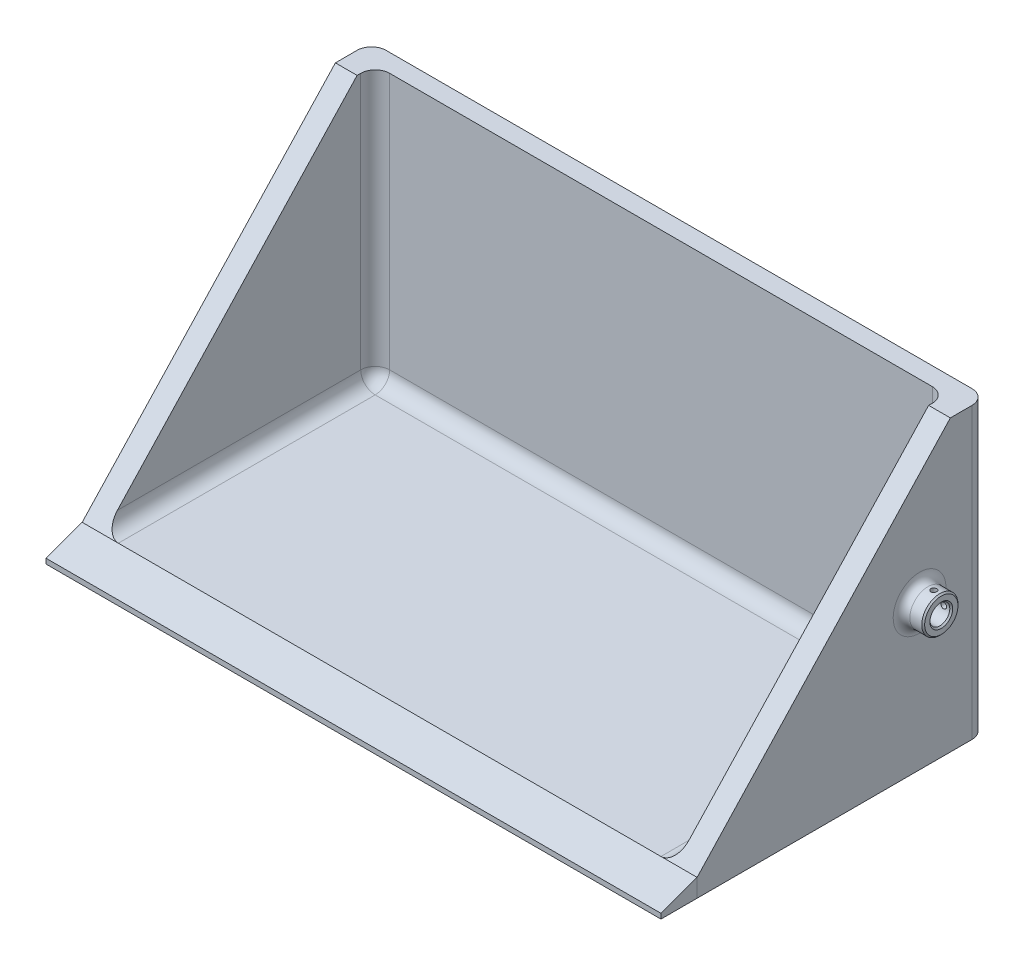
SolidWorks part; units mm, degrees
ref_plane "Front Plane" through (0, 0, 0) normal (0, 0, 1) x (1, 0, 0)
ref_plane "Top Plane" through (0, 0, 0) normal (0, 1, 0) x (1, 0, 0)
ref_plane "Right Plane" through (0, 0, 0) normal (1, 0, 0) x (0, 0, -1)
sketch "Sketch1" plane through (0, 0, 0) normal (0, 1, 0) x (1, 0, 0)
  line L1 (-107.95, 50.8) -> (107.95, 50.8)
  line L2 (-107.95, 50.8) -> (-107.95, -50.8)
  line L3 (-107.95, -50.8) -> (107.95, -50.8)
  line L4 (107.95, 50.8) -> (107.95, -50.8)
  line L5 (-107.95, 50.8) -> (107.95, -50.8) construction
  line L6 (-107.95, -50.8) -> (107.95, 50.8) construction
  point P0 (0, 0)
  dimension "D1" = 215.9
  dimension "D2" = 101.6
extrude "Boss-Extrude1" add sketch "Sketch1" along normal mid plane 6.35
sketch "Sketch3" plane through (-107.95, 0, 0) normal (-1, 0, 0) x (0, 0, 1)
  line L0 (-50.8, 3.175) -> (-50.8, 98.425)
  line L1 (-50.8, 98.425) -> (-38.1, 98.425)
  line L2 (-38.1, 98.425) -> (50.8, 3.175)
  line L3 (50.8, 3.175) -> (-50.8, 3.175)
  line L4 (-50.8, -3.175) -> (50.8, -3.175) construction
  dimension "D1" = 101.6
  dimension "D2" = 12.7
extrude "Boss-Extrude2" add sketch "Sketch3" against normal blind 7.62
mirror "Mirror1" about plane through (0, 0, 0) normal (1, 0, 0) of "Boss-Extrude2"
sketch "Sketch4" plane through (0, 3.175, 0) normal (0, 1, 0) x (1, 0, 0)
  line L0 (-100.33, 50.8) -> (100.33, 50.8)
  line L1 (100.33, 50.8) -> (100.33, 44.45)
  line L2 (100.33, 44.45) -> (-100.33, 44.45)
  line L3 (-100.33, 44.45) -> (-100.33, 50.8)
  dimension "D1" = 6.35
extrude "Boss-Extrude3" add sketch "Sketch4" along normal up to surface (95.25 mm away) up to face at (-104.14, 98.425, -44.45)
sketch "Sketch5" plane through (-107.95, 0, 0) normal (-1, 0, 0) x (0, 0, 1)
  line L1 (63.5, -3.175) -> (50.8, -3.175)
  line L2 (50.8, -3.175) -> (50.8, 3.175)
  line L3 (-50.8, 98.425) -> (-50.8, -3.175) construction
  line L4 (50.8, 3.175) -> (63.5, -1.397)
  line L5 (63.5, -1.397) -> (63.5, -3.175)
  dimension "D1" = 114.3
  dimension "D2" = 1.778
extrude "Boss-Extrude4" add sketch "Sketch5" along direction (1, 0, 0) on the side against the normal up to surface (215.9 mm away) separate body
fillet "Fillet2" radius 5.08 5 edges at (100.33, 3.175, 3.175) (100.33, 50.8, -44.45) (0, 3.175, -44.45) (-100.33, 3.175, 3.175) (-100.33, 50.8, -44.45)
fillet "Fillet3" radius 5.08 2 edges at (107.95, 47.625, -50.8) (-107.95, 47.625, -50.8)
sketch "Sketch6" plane through (107.95, 0, 0) normal (1, 0, 0) x (0, 0, -1)
  line L0 (-50.8, -3.175) -> (45.72, -3.175) construction
  line L1 (50.8, 98.425) -> (50.8, -3.175) construction
  circle A0 centre (27.305, 47.625) radius 3.4925
  circle A1 centre (27.305, 47.625) radius 6.35
  dimension "D1" = 6.985
  dimension "D2" = 12.7
  dimension "D3" = 50.8
  dimension "D4" = 23.495
extrude "Boss-Extrude5" add sketch "Sketch6" along normal blind 7.62
fillet "Fillet4" radius 2.921 1 edges at (107.95, 47.625, -20.955)
chamfer "Chamfer1" distance 0.508 angle 45 2 edges at (115.57, 47.625, -30.7975) (115.57, 47.625, -33.655)
ref_plane "setscrew_lhs_plane" through (0, 53.975, 0) normal (0, 1, 0) x (1, 0, 0)
sketch "Sketch7" plane through (0, 53.975, 0) normal (0, 1, 0) x (1, 0, 0)
  line L0 (110.871, 20.955) -> (115.062, 20.955) construction
  line L1 (115.062, 33.655) -> (110.871, 33.655) construction
  line L2 (110.871, 20.955) -> (115.062, 20.955) construction
  line L3 (115.062, 33.655) -> (110.871, 33.655) construction
  line L4 (112.9665, 33.655) -> (112.9665, 20.955) construction
  circle A0 centre (112.9665, 27.305) radius 1.0033
  dimension "D1" = 2.0066
extrude "Cut-Extrude1" cut sketch "Sketch7" against normal blind 3.81
pattern_circular "CirPattern1" count 2 every 90 about axis through (115.57, 47.625, -27.305) along (-1, 0, 0) of "Cut-Extrude1"
